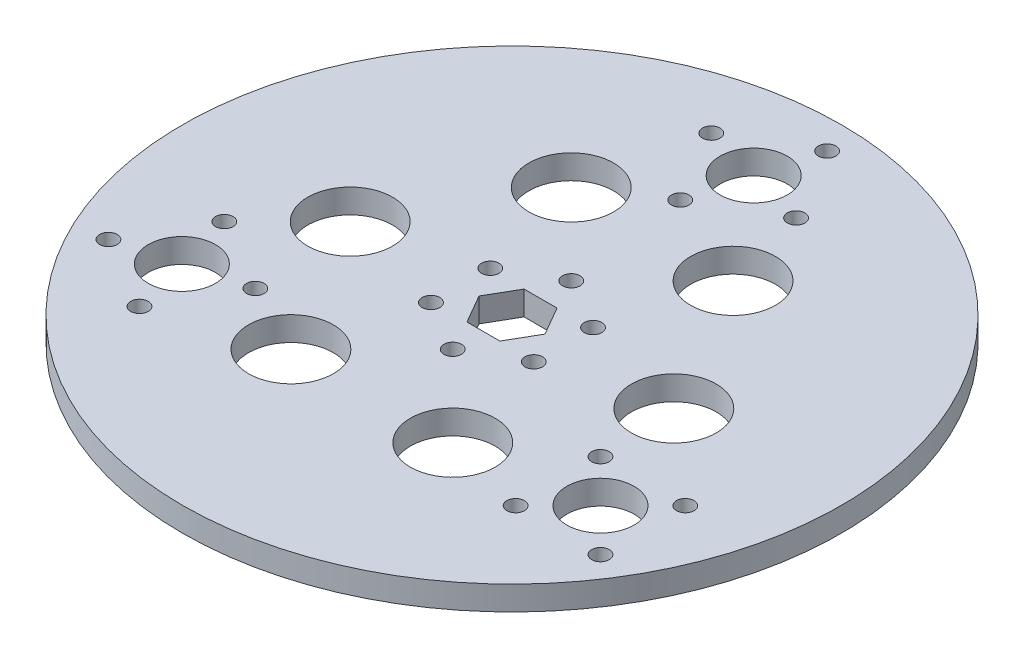
SolidWorks part; units mm, degrees
ref_plane "Front Plane" through (0, 0, 0) normal (0, 0, 1) x (1, 0, 0)
ref_plane "Top Plane" through (0, 0, 0) normal (0, 1, 0) x (1, 0, 0)
ref_plane "Right Plane" through (0, 0, 0) normal (1, 0, 0) x (0, 0, -1)
sketch "Sketch4" plane through (0, 0, 0) normal (0, 1, 0) x (1, 0, 0)
  line L0 (0, 55) -> (0, 0) construction
  line L1 (18.4137, -31.8935) -> (36.8274, 0) construction
  line L2 (36.8274, 0) -> (18.4137, 31.8935) construction
  line L3 (18.4137, 31.8935) -> (-18.4137, 31.8935) construction
  line L4 (-18.4137, 31.8935) -> (-36.8274, 0) construction
  line L5 (-36.8274, 0) -> (-18.4137, -31.8935) construction
  line L6 (-18.4137, -31.8935) -> (18.4137, -31.8935) construction
  line L7 (0, 0) -> (-47.6314, -27.5) construction
  line L8 (0, 0) -> (47.6314, -27.5) construction
  line L10 (3.7528, -6.5) -> (7.5056, 0)
  line L11 (7.5056, 0) -> (3.7528, 6.5)
  line L12 (3.7528, 6.5) -> (-3.7528, 6.5)
  line L13 (-3.7528, 6.5) -> (-7.5056, 0)
  line L14 (-7.5056, 0) -> (-3.7528, -6.5)
  line L15 (-3.7528, -6.5) -> (3.7528, -6.5)
  line L16 (37.9794, -37.152) -> (57.2834, -37.152) construction
  line L17 (37.9794, -37.152) -> (37.9794, -17.848) construction
  line L18 (37.9794, -17.848) -> (57.2834, -17.848) construction
  line L19 (57.2834, -37.152) -> (57.2834, -17.848) construction
  line L20 (37.9794, -37.152) -> (57.2834, -17.848) construction
  line L21 (37.9794, -17.848) -> (57.2834, -37.152) construction
  circle A0 centre (0, 0) radius 31.8935 construction
  circle A1 centre (-36.8274, 0) radius 9.65
  circle A2 centre (-18.4137, 31.8935) radius 9.65
  circle A3 centre (18.4137, 31.8935) radius 9.65
  circle A4 centre (36.8274, 0) radius 9.65
  circle A5 centre (18.4137, -31.8935) radius 9.65
  circle A6 centre (-18.4137, -31.8935) radius 9.65
  circle A7 centre (0, 0) radius 75
  circle A11 centre (0, 0) radius 6.5 construction
  circle A12 centre (0, 13.5) radius 2
  circle A13 centre (11.6913, 6.75) radius 2
  circle A14 centre (11.6913, -6.75) radius 2
  circle A15 centre (0, -13.5) radius 2
  circle A16 centre (-11.6913, -6.75) radius 2
  circle A17 centre (-11.6913, 6.75) radius 2
  circle A19 centre (0, 55) radius 7.65
  circle A20 centre (47.6314, -27.5) radius 7.65
  circle A21 centre (-47.6314, -27.5) radius 7.65
  circle A22 centre (37.9794, -37.152) radius 2
  circle A23 centre (37.9794, -17.848) radius 2
  circle A24 centre (57.2834, -17.848) radius 2
  circle A25 centre (57.2834, -37.152) radius 2
  circle A26 centre (-51.1643, -14.3151) radius 2
  circle A27 centre (-60.8163, -31.0329) radius 2
  circle A28 centre (-44.0985, -40.6849) radius 2
  circle A29 centre (-34.4465, -23.9671) radius 2
  circle A30 centre (13.1849, 51.4671) radius 2
  circle A31 centre (3.5329, 68.1849) radius 2
  circle A32 centre (-13.1849, 58.5329) radius 2
  circle A33 centre (-3.5329, 41.8151) radius 2
  point P22 (0, 0)
  point P47 (0, 0)
  point P50 (0, 0)
  point P63 (47.6314, -27.5)
  point P80 (0, 0)
  dimension "D1" = 19.3
  dimension "D3" = 150
  dimension "D6" = 55
  dimension "D8" = 4
  dimension "D11" = 15.3
  dimension "D14" = 4
  dimension "D4" = 120
  dimension "D5" = 120
  dimension "D7" = 13
  dimension "D9" = 5
  dimension "D13" = 13.65
  dimension "D2" = 6
  dimension "D10" = 6
  dimension "D12" = 3
  dimension "D15" = 4
  dimension "D16" = 3
extrude "Boss-Extrude1" add sketch "Sketch4" along normal blind 5.5
